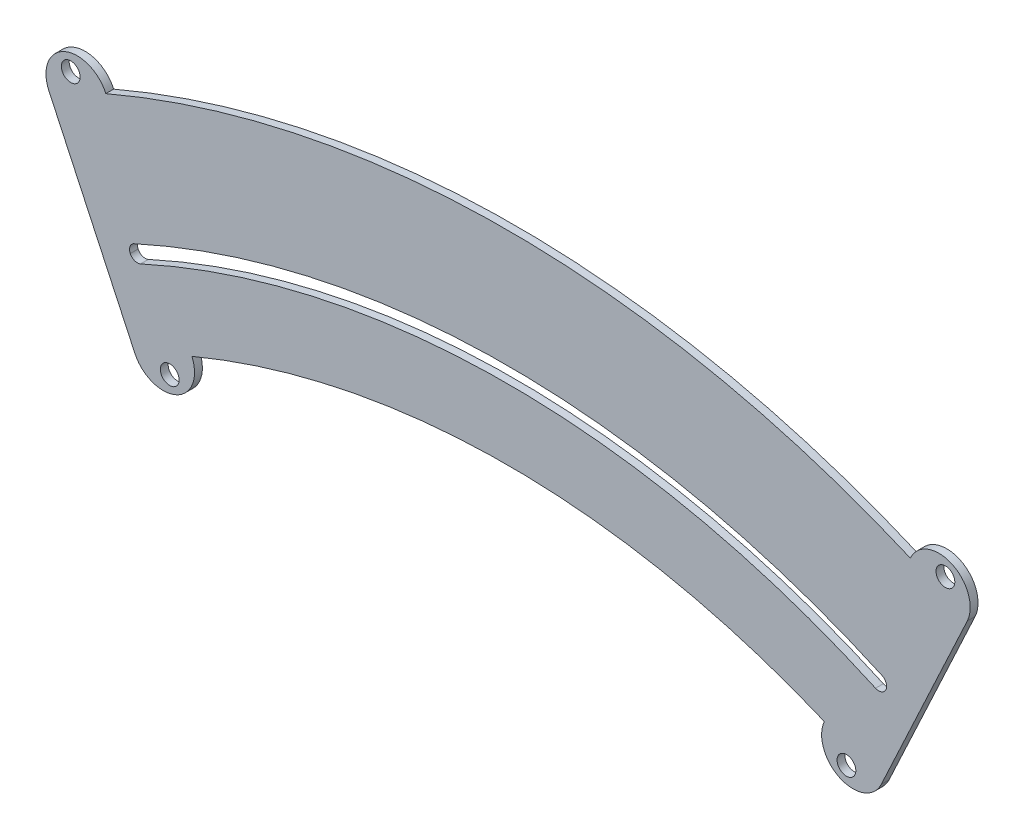
SolidWorks part; units mm, degrees
ref_plane "Płaszczyzna przednia" through (0, 0, 0) normal (0, 0, 1) x (1, 0, 0)
ref_plane "Płaszczyzna górna" through (0, 0, 0) normal (0, 1, 0) x (1, 0, 0)
ref_plane "Płaszczyzna prawa" through (0, 0, 0) normal (1, 0, 0) x (0, 0, -1)
sketch "Szkic1" plane through (0, 0, 0) normal (0, 0, 1) x (1, 0, 0)
  line L1 (220.3278, 472.4945) -> (275.2682, 590.3145)
  line L2 (-220.3278, 472.4945) -> (-275.2682, 590.3145)
  arc A0 (241.4587, 517.8099) -> (-241.4587, 517.8099) centre (0, 0) ccw
  arc A1 (275.2682, 590.3145) -> (-275.2682, 590.3145) centre (0, 0) ccw
  arc A2 (220.3278, 472.4945) -> (-220.3278, 472.4945) centre (0, 0) ccw
  dimension "D1" = 1142.68
  dimension "D2" = 80
  dimension "D3" = 50
extrude "Dodanie-wyciągnięcie1" add sketch "Szkic1" along normal blind 5 contours L1 A1 L2 A0 | A2 L1 A0 L2
sketch "Szkic2" plane through (0, 0, 5) normal (0, 0, 1) x (1, 0, 0)
  line L8 (-293.3943, 581.8621) -> (-238.454, 464.0421)
  line L9 (293.3943, 581.8621) -> (238.454, 464.0421)
  circle A0 centre (-279.4247, 599.4098) radius 6
  circle A1 centre (-216.1887, 463.3913) radius 6
  circle A2 centre (216.1887, 463.3913) radius 6
  arc A4 (293.3943, 581.8621) -> (257.0144, 598.4876) centre (275.2682, 590.3145) ccw
  arc A5 (202.0429, 480.5976) -> (238.454, 464.0421) centre (220.3278, 472.4945) ccw
  arc A6 (-257.0144, 598.4876) -> (-293.3943, 581.8621) centre (-275.2682, 590.3145) ccw
  arc A7 (-238.454, 464.0421) -> (-202.0429, 480.5976) centre (-220.3278, 472.4945) ccw
  arc A8 (-257.0144, 598.4876) -> (257.0144, 598.4876) centre (0, 0) cw
  arc A9 (275.2682, 590.3145) -> (-275.2682, 590.3145) centre (0, 0) ccw construction
  arc A10 (-202.0429, 480.5976) -> (202.0429, 480.5976) centre (0, 0) cw
  arc A11 (220.3278, 472.4945) -> (-220.3278, 472.4945) centre (0, 0) ccw construction
  circle A12 centre (279.4247, 599.4098) radius 6
  dimension "D3" = 12
  dimension "D1" = 12
  dimension "D2" = 12
  dimension "D4" = 12
extrude "Dodanie-wyciągnięcie2" add sketch "Szkic2" against normal blind 5
sketch "Szkic4" plane through (0, 0, 5) normal (0, 0, 1) x (1, 0, 0)
  line L0 (241.3801, 517.7983) -> (241.3986, 517.8379)
  line L2 (-241.3801, 517.7983) -> (-241.3986, 517.8379)
  arc A1 (238.9305, 524.4807) -> (-238.9305, 524.4807) centre (0, 0) ccw
  arc A2 (234.7848, 515.3805) -> (-234.7848, 515.3805) centre (0, 0) ccw
  arc A6 (-238.9305, 524.4807) -> (-234.7848, 515.3805) centre (-236.8576, 519.9306) ccw
  arc A7 (234.7848, 515.3805) -> (238.9305, 524.4807) centre (236.8576, 519.9306) ccw
  dimension "D4" = 10
  dimension "D5" = 10
extrude "Wytnij-wyciągnięcie1" cut sketch "Szkic4" against normal through all contours A2 A7 L0 A1 A6 L2
